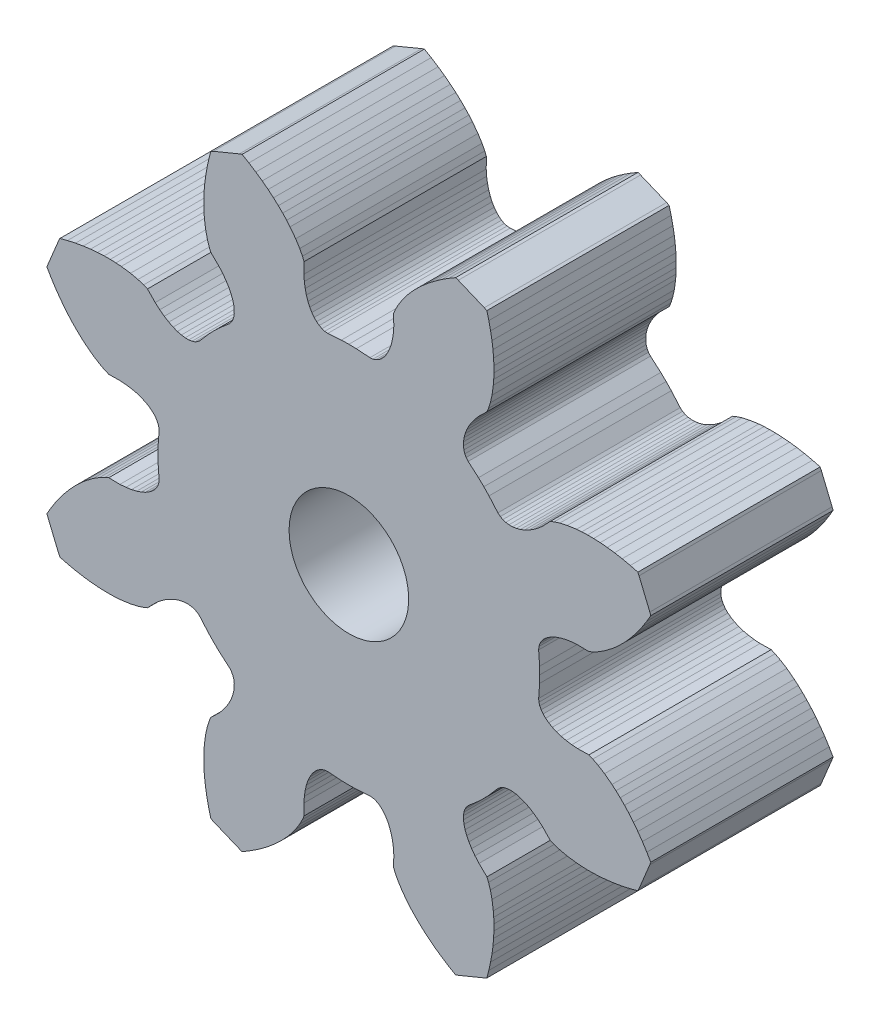
SolidWorks part; units mm, degrees
ref_plane "Front Plane" through (0, 0, 0) normal (0, 0, 1) x (1, 0, 0)
ref_plane "Top Plane" through (0, 0, 0) normal (0, 1, 0) x (1, 0, 0)
ref_plane "Right Plane" through (0, 0, 0) normal (1, 0, 0) x (0, 0, -1)
sketch "Sketch1" plane through (0, 0, 0) normal (0, 0, 1) x (1, 0, 0)
  line L0 (-6.534, 0.0723) -> (-6.5708, 0.241)
  line L1 (-6.5708, 0.241) -> (-6.599, 0.4026)
  line L2 (-6.599, 0.4026) -> (-6.6194, 0.5555)
  line L3 (-6.6194, 0.5555) -> (-6.6332, 0.701)
  line L4 (-6.6332, 0.701) -> (-6.6396, 0.8379)
  line L5 (-6.6396, 0.8379) -> (-6.6404, 0.9662)
  line L6 (-6.6404, 0.9662) -> (-6.6361, 1.0857)
  line L7 (-6.6361, 1.0857) -> (-6.6274, 1.1966)
  line L8 (-6.6274, 1.1966) -> (-6.6004, 1.3892)
  line L9 (-6.6004, 1.3892) -> (-6.5651, 1.5443)
  line L10 (-6.5651, 1.5443) -> (-6.5282, 1.6631)
  line L11 (-6.5282, 1.6631) -> (-6.494, 1.745)
  line L12 (-6.494, 1.745) -> (-6.3281, 1.9057)
  line L13 (-6.3281, 1.9057) -> (-6.2449, 2.0013)
  line L14 (-6.2449, 2.0013) -> (-6.1745, 2.0963)
  line L15 (-6.1745, 2.0963) -> (-6.1173, 2.1897)
  line L16 (-6.1173, 2.1897) -> (-6.0718, 2.2811)
  line L17 (-6.0718, 2.2811) -> (-6.0376, 2.3695)
  line L18 (-6.0376, 2.3695) -> (-6.0152, 2.4535)
  line L19 (-6.0152, 2.4535) -> (-6.0042, 2.5332)
  line L20 (-6.0042, 2.5332) -> (-6.0036, 2.607)
  line L21 (-6.0036, 2.607) -> (-6.0129, 2.6744)
  line L22 (-6.0129, 2.6744) -> (-6.0327, 2.7352)
  line L23 (-6.0327, 2.7352) -> (-6.0609, 2.7889)
  line L24 (-6.0609, 2.7889) -> (-6.1021, 2.8388)
  line L25 (-6.1021, 2.8388) -> (-6.3174, 3.0243)
  line L26 (-6.3174, 3.0243) -> (-6.4295, 3.133)
  line L27 (-6.4295, 3.133) -> (-6.5374, 3.2453)
  line L28 (-6.5374, 3.2453) -> (-6.7237, 3.4597)
  line L29 (-6.7237, 3.4597) -> (-6.7738, 3.5017)
  line L30 (-6.7738, 3.5017) -> (-6.8265, 3.53)
  line L31 (-6.8265, 3.53) -> (-6.8874, 3.5488)
  line L32 (-6.8874, 3.5488) -> (-6.9547, 3.5583)
  line L33 (-6.9547, 3.5583) -> (-7.0287, 3.5583)
  line L34 (-7.0287, 3.5583) -> (-7.1085, 3.5467)
  line L35 (-7.1085, 3.5467) -> (-7.1925, 3.5242)
  line L36 (-7.1925, 3.5242) -> (-7.2808, 3.4908)
  line L37 (-7.2808, 3.4908) -> (-7.372, 3.4452)
  line L38 (-7.372, 3.4452) -> (-7.4654, 3.3872)
  line L39 (-7.4654, 3.3872) -> (-7.5612, 3.317)
  line L40 (-7.5612, 3.317) -> (-7.6561, 3.2345)
  line L41 (-7.6561, 3.2345) -> (-7.8169, 3.0678)
  line L42 (-7.8169, 3.0678) -> (-7.8987, 3.0344)
  line L43 (-7.8987, 3.0344) -> (-8.0176, 2.9968)
  line L44 (-8.0176, 2.9968) -> (-8.1726, 2.9613)
  line L45 (-8.1726, 2.9613) -> (-8.3661, 2.9344)
  line L46 (-8.3661, 2.9344) -> (-8.4762, 2.9257)
  line L47 (-8.4762, 2.9257) -> (-8.5956, 2.9215)
  line L48 (-8.5956, 2.9215) -> (-8.7238, 2.9229)
  line L49 (-8.7238, 2.9229) -> (-8.8608, 2.9294)
  line L50 (-8.8608, 2.9294) -> (-9.0064, 2.9424)
  line L51 (-9.0064, 2.9424) -> (-9.1599, 2.9627)
  line L52 (-9.1599, 2.9627) -> (-9.3208, 2.991)
  line L53 (-9.3208, 2.991) -> (-9.4895, 3.0279)
  line L54 (-9.4895, 3.0279) -> (-9.6482, 3.07)
  line L55 (-9.6482, 3.07) -> (-9.6737, 3.1235)
  line L56 (-9.6737, 3.1235) -> (-9.8989, 3.6668)
  line L57 (-9.8989, 3.6668) -> (-9.9185, 3.722)
  line L58 (-9.9185, 3.722) -> (-9.836, 3.8639)
  line L59 (-9.836, 3.8639) -> (-9.7433, 4.0096)
  line L60 (-9.7433, 4.0096) -> (-9.649, 4.1435)
  line L61 (-9.649, 4.1435) -> (-9.5548, 4.266)
  line L62 (-9.5548, 4.266) -> (-9.4613, 4.3783)
  line L63 (-9.4613, 4.3783) -> (-9.3693, 4.4797)
  line L64 (-9.3693, 4.4797) -> (-9.2789, 4.5709)
  line L65 (-9.2789, 4.5709) -> (-9.1912, 4.6528)
  line L66 (-9.1912, 4.6528) -> (-9.1072, 4.7246)
  line L67 (-9.1072, 4.7246) -> (-8.952, 4.842)
  line L68 (-8.952, 4.842) -> (-8.8173, 4.9268)
  line L69 (-8.8173, 4.9268) -> (-8.7066, 4.9838)
  line L70 (-8.7066, 4.9838) -> (-8.6253, 5.0188)
  line L71 (-8.6253, 5.0188) -> (-8.3935, 5.0143)
  line L72 (-8.3935, 5.0143) -> (-8.2675, 5.0237)
  line L73 (-8.2675, 5.0237) -> (-8.151, 5.0412)
  line L74 (-8.151, 5.0412) -> (-8.0435, 5.0665)
  line L75 (-8.0435, 5.0665) -> (-7.9472, 5.0983)
  line L76 (-7.9472, 5.0983) -> (-7.8611, 5.1367)
  line L77 (-7.8611, 5.1367) -> (-7.7858, 5.181)
  line L78 (-7.7858, 5.181) -> (-7.7211, 5.2287)
  line L79 (-7.7211, 5.2287) -> (-7.6684, 5.2809)
  line L80 (-7.6684, 5.2809) -> (-7.627, 5.3361)
  line L81 (-7.627, 5.3361) -> (-7.598, 5.3924)
  line L82 (-7.598, 5.3924) -> (-7.5807, 5.4497)
  line L83 (-7.5807, 5.4497) -> (-7.5749, 5.5143)
  line L84 (-7.5749, 5.5143) -> (-7.5952, 5.7982)
  line L85 (-7.5952, 5.7982) -> (-7.598, 5.954)
  line L86 (-7.598, 5.954) -> (-7.5952, 6.1096)
  line L87 (-7.5952, 6.1096) -> (-7.5749, 6.3929)
  line L88 (-7.5749, 6.3929) -> (-7.5807, 6.4581)
  line L89 (-7.5807, 6.4581) -> (-7.598, 6.5154)
  line L90 (-7.598, 6.5154) -> (-7.627, 6.572)
  line L91 (-7.627, 6.572) -> (-7.6684, 6.627)
  line L92 (-7.6684, 6.627) -> (-7.7211, 6.6784)
  line L93 (-7.7211, 6.6784) -> (-7.7858, 6.727)
  line L94 (-7.7858, 6.727) -> (-7.8611, 6.7704)
  line L95 (-7.8611, 6.7704) -> (-7.9472, 6.8087)
  line L96 (-7.9472, 6.8087) -> (-8.0435, 6.8415)
  line L97 (-8.0435, 6.8415) -> (-8.151, 6.8668)
  line L98 (-8.151, 6.8668) -> (-8.2675, 6.8841)
  line L99 (-8.2675, 6.8841) -> (-8.3935, 6.8927)
  line L100 (-8.3935, 6.8927) -> (-8.6253, 6.8893)
  line L101 (-8.6253, 6.8893) -> (-8.7066, 6.9232)
  line L102 (-8.7066, 6.9232) -> (-8.8173, 6.9813)
  line L103 (-8.8173, 6.9813) -> (-8.952, 7.0661)
  line L104 (-8.952, 7.0661) -> (-9.1072, 7.1834)
  line L105 (-9.1072, 7.1834) -> (-9.1912, 7.255)
  line L106 (-9.1912, 7.255) -> (-9.2789, 7.337)
  line L107 (-9.2789, 7.337) -> (-9.3693, 7.4274)
  line L108 (-9.3693, 7.4274) -> (-9.4613, 7.5289)
  line L109 (-9.4613, 7.5289) -> (-9.5548, 7.6418)
  line L110 (-9.5548, 7.6418) -> (-9.649, 7.7643)
  line L111 (-9.649, 7.7643) -> (-9.7433, 7.8983)
  line L112 (-9.7433, 7.8983) -> (-9.836, 8.0439)
  line L113 (-9.836, 8.0439) -> (-9.9185, 8.1852)
  line L114 (-9.9185, 8.1852) -> (-9.8989, 8.2411)
  line L115 (-9.8989, 8.2411) -> (-9.6737, 8.785)
  line L116 (-9.6737, 8.785) -> (-9.6482, 8.8378)
  line L117 (-9.6482, 8.8378) -> (-9.4895, 8.8799)
  line L118 (-9.4895, 8.8799) -> (-9.3208, 8.9169)
  line L119 (-9.3208, 8.9169) -> (-9.1599, 8.9452)
  line L120 (-9.1599, 8.9452) -> (-9.0064, 8.9654)
  line L121 (-9.0064, 8.9654) -> (-8.8608, 8.9784)
  line L122 (-8.8608, 8.9784) -> (-8.7238, 8.9849)
  line L123 (-8.7238, 8.9849) -> (-8.5956, 8.9857)
  line L124 (-8.5956, 8.9857) -> (-8.4762, 8.9814)
  line L125 (-8.4762, 8.9814) -> (-8.3661, 8.9734)
  line L126 (-8.3661, 8.9734) -> (-8.1726, 8.9457)
  line L127 (-8.1726, 8.9457) -> (-8.0176, 8.9111)
  line L128 (-8.0176, 8.9111) -> (-7.8987, 8.8735)
  line L129 (-7.8987, 8.8735) -> (-7.8169, 8.8401)
  line L130 (-7.8169, 8.8401) -> (-7.6561, 8.6735)
  line L131 (-7.6561, 8.6735) -> (-7.5612, 8.5908)
  line L132 (-7.5612, 8.5908) -> (-7.4654, 8.5206)
  line L133 (-7.4654, 8.5206) -> (-7.372, 8.4626)
  line L134 (-7.372, 8.4626) -> (-7.2808, 8.4171)
  line L135 (-7.2808, 8.4171) -> (-7.1925, 8.3829)
  line L136 (-7.1925, 8.3829) -> (-7.1085, 8.3613)
  line L137 (-7.1085, 8.3613) -> (-7.0287, 8.3497)
  line L138 (-7.0287, 8.3497) -> (-6.9547, 8.349)
  line L139 (-6.9547, 8.349) -> (-6.8874, 8.359)
  line L140 (-6.8874, 8.359) -> (-6.8265, 8.3778)
  line L141 (-6.8265, 8.3778) -> (-6.7738, 8.4061)
  line L142 (-6.7738, 8.4061) -> (-6.7237, 8.4482)
  line L143 (-6.7237, 8.4482) -> (-6.5374, 8.6625)
  line L144 (-6.5374, 8.6625) -> (-6.4295, 8.7749)
  line L145 (-6.4295, 8.7749) -> (-6.3174, 8.8828)
  line L146 (-6.3174, 8.8828) -> (-6.1021, 9.0691)
  line L147 (-6.1021, 9.0691) -> (-6.0609, 9.119)
  line L148 (-6.0609, 9.119) -> (-6.0327, 9.1718)
  line L149 (-6.0327, 9.1718) -> (-6.0129, 9.2327)
  line L150 (-6.0129, 9.2327) -> (-6.0036, 9.3009)
  line L151 (-6.0036, 9.3009) -> (-6.0042, 9.3748)
  line L152 (-6.0042, 9.3748) -> (-6.0152, 9.4545)
  line L153 (-6.0152, 9.4545) -> (-6.0376, 9.5385)
  line L154 (-6.0376, 9.5385) -> (-6.0718, 9.6267)
  line L155 (-6.0718, 9.6267) -> (-6.1173, 9.7182)
  line L156 (-6.1173, 9.7182) -> (-6.1745, 9.8115)
  line L157 (-6.1745, 9.8115) -> (-6.2449, 9.9065)
  line L158 (-6.2449, 9.9065) -> (-6.3281, 10.0021)
  line L159 (-6.3281, 10.0021) -> (-6.494, 10.163)
  line L160 (-6.494, 10.163) -> (-6.5282, 10.2447)
  line L161 (-6.5282, 10.2447) -> (-6.5651, 10.3635)
  line L162 (-6.5651, 10.3635) -> (-6.6004, 10.5186)
  line L163 (-6.6004, 10.5186) -> (-6.6274, 10.7114)
  line L164 (-6.6274, 10.7114) -> (-6.6361, 10.8214)
  line L165 (-6.6361, 10.8214) -> (-6.6404, 10.9417)
  line L166 (-6.6404, 10.9417) -> (-6.6396, 11.07)
  line L167 (-6.6396, 11.07) -> (-6.6332, 11.2061)
  line L168 (-6.6332, 11.2061) -> (-6.6194, 11.3524)
  line L169 (-6.6194, 11.3524) -> (-6.599, 11.5052)
  line L170 (-6.599, 11.5052) -> (-6.5708, 11.6668)
  line L171 (-6.5708, 11.6668) -> (-6.534, 11.835)
  line L172 (-6.534, 11.835) -> (-6.4926, 11.9943)
  line L173 (-6.4926, 11.9943) -> (-6.4397, 12.0197)
  line L174 (-6.4397, 12.0197) -> (-5.8956, 12.2451)
  line L175 (-5.8956, 12.2451) -> (-5.84, 12.2644)
  line L176 (-5.84, 12.2644) -> (-5.6979, 12.1812)
  line L177 (-5.6979, 12.1812) -> (-5.5531, 12.0884)
  line L178 (-5.5531, 12.0884) -> (-5.419, 11.9943)
  line L179 (-5.419, 11.9943) -> (-5.2959, 11.9008)
  line L180 (-5.2959, 11.9008) -> (-5.1836, 11.8066)
  line L181 (-5.1836, 11.8066) -> (-5.0822, 11.7146)
  line L182 (-5.0822, 11.7146) -> (-4.9909, 11.6248)
  line L183 (-4.9909, 11.6248) -> (-4.9089, 11.5371)
  line L184 (-4.9089, 11.5371) -> (-4.8372, 11.4531)
  line L185 (-4.8372, 11.4531) -> (-4.72, 11.2973)
  line L186 (-4.72, 11.2973) -> (-4.6352, 11.1627)
  line L187 (-4.6352, 11.1627) -> (-4.5779, 11.0525)
  line L188 (-4.5779, 11.0525) -> (-4.5438, 10.9705)
  line L189 (-4.5438, 10.9705) -> (-4.5475, 10.7395)
  line L190 (-4.5475, 10.7395) -> (-4.5388, 10.6136)
  line L191 (-4.5388, 10.6136) -> (-4.5206, 10.4961)
  line L192 (-4.5206, 10.4961) -> (-4.4962, 10.3897)
  line L193 (-4.4962, 10.3897) -> (-4.4635, 10.2925)
  line L194 (-4.4635, 10.2925) -> (-4.4251, 10.2064)
  line L195 (-4.4251, 10.2064) -> (-4.3808, 10.1311)
  line L196 (-4.3808, 10.1311) -> (-4.3331, 10.0664)
  line L197 (-4.3331, 10.0664) -> (-4.2808, 10.0144)
  line L198 (-4.2808, 10.0144) -> (-4.2265, 9.9732)
  line L199 (-4.2265, 9.9732) -> (-4.1701, 9.9433)
  line L200 (-4.1701, 9.9433) -> (-4.112, 9.9261)
  line L201 (-4.112, 9.9261) -> (-4.0477, 9.9201)
  line L202 (-4.0477, 9.9201) -> (-3.7643, 9.9405)
  line L203 (-3.7643, 9.9405) -> (-3.6079, 9.9433)
  line L204 (-3.6079, 9.9433) -> (-3.4523, 9.9405)
  line L205 (-3.4523, 9.9405) -> (-3.1688, 9.9201)
  line L206 (-3.1688, 9.9201) -> (-3.1044, 9.9261)
  line L207 (-3.1044, 9.9261) -> (-3.0465, 9.9433)
  line L208 (-3.0465, 9.9433) -> (-2.9898, 9.9732)
  line L209 (-2.9898, 9.9732) -> (-2.9358, 10.0144)
  line L210 (-2.9358, 10.0144) -> (-2.8834, 10.0664)
  line L211 (-2.8834, 10.0664) -> (-2.835, 10.1311)
  line L212 (-2.835, 10.1311) -> (-2.7914, 10.2064)
  line L213 (-2.7914, 10.2064) -> (-2.7531, 10.2925)
  line L214 (-2.7531, 10.2925) -> (-2.7204, 10.3897)
  line L215 (-2.7204, 10.3897) -> (-2.6952, 10.4961)
  line L216 (-2.6952, 10.4961) -> (-2.6778, 10.6136)
  line L217 (-2.6778, 10.6136) -> (-2.669, 10.7395)
  line L218 (-2.669, 10.7395) -> (-2.6727, 10.9705)
  line L219 (-2.6727, 10.9705) -> (-2.6387, 11.0525)
  line L220 (-2.6387, 11.0525) -> (-2.5813, 11.1627)
  line L221 (-2.5813, 11.1627) -> (-2.4966, 11.2973)
  line L222 (-2.4966, 11.2973) -> (-2.3794, 11.4531)
  line L223 (-2.3794, 11.4531) -> (-2.3069, 11.5371)
  line L224 (-2.3069, 11.5371) -> (-2.2255, 11.6248)
  line L225 (-2.2255, 11.6248) -> (-2.1343, 11.7146)
  line L226 (-2.1343, 11.7146) -> (-2.0329, 11.8066)
  line L227 (-2.0329, 11.8066) -> (-1.9207, 11.9008)
  line L228 (-1.9207, 11.9008) -> (-1.7976, 11.9943)
  line L229 (-1.7976, 11.9943) -> (-1.6635, 12.0884)
  line L230 (-1.6635, 12.0884) -> (-1.5186, 12.1812)
  line L231 (-1.5186, 12.1812) -> (-1.3766, 12.2644)
  line L232 (-1.3766, 12.2644) -> (-1.3215, 12.2451)
  line L233 (-1.3215, 12.2451) -> (-0.7776, 12.0197)
  line L234 (-0.7776, 12.0197) -> (-0.724, 11.9943)
  line L235 (-0.724, 11.9943) -> (-0.6826, 11.835)
  line L236 (-0.6826, 11.835) -> (-0.6458, 11.6668)
  line L237 (-0.6458, 11.6668) -> (-0.6168, 11.5052)
  line L238 (-0.6168, 11.5052) -> (-0.5964, 11.3524)
  line L239 (-0.5964, 11.3524) -> (-0.5834, 11.2061)
  line L240 (-0.5834, 11.2061) -> (-0.5769, 11.07)
  line L241 (-0.5769, 11.07) -> (-0.5762, 10.9417)
  line L242 (-0.5762, 10.9417) -> (-0.5805, 10.8214)
  line L243 (-0.5805, 10.8214) -> (-0.5891, 10.7114)
  line L244 (-0.5891, 10.7114) -> (-0.616, 10.5186)
  line L245 (-0.616, 10.5186) -> (-0.6507, 10.3635)
  line L246 (-0.6507, 10.3635) -> (-0.6884, 10.2447)
  line L247 (-0.6884, 10.2447) -> (-0.7225, 10.163)
  line L248 (-0.7225, 10.163) -> (-0.8883, 10.0021)
  line L249 (-0.8883, 10.0021) -> (-0.9717, 9.9065)
  line L250 (-0.9717, 9.9065) -> (-1.0413, 9.8115)
  line L251 (-1.0413, 9.8115) -> (-1.0991, 9.7182)
  line L252 (-1.0991, 9.7182) -> (-1.1448, 9.6267)
  line L253 (-1.1448, 9.6267) -> (-1.1789, 9.5385)
  line L254 (-1.1789, 9.5385) -> (-1.2014, 9.4545)
  line L255 (-1.2014, 9.4545) -> (-1.2123, 9.3748)
  line L256 (-1.2123, 9.3748) -> (-1.2129, 9.3009)
  line L257 (-1.2129, 9.3009) -> (-1.2035, 9.2327)
  line L258 (-1.2035, 9.2327) -> (-1.1839, 9.1718)
  line L259 (-1.1839, 9.1718) -> (-1.1557, 9.119)
  line L260 (-1.1557, 9.119) -> (-1.1143, 9.0691)
  line L261 (-1.1143, 9.0691) -> (-0.8992, 8.8828)
  line L262 (-0.8992, 8.8828) -> (-0.787, 8.7749)
  line L263 (-0.787, 8.7749) -> (-0.6791, 8.6625)
  line L264 (-0.6791, 8.6625) -> (-0.4929, 8.4482)
  line L265 (-0.4929, 8.4482) -> (-0.4428, 8.4061)
  line L266 (-0.4428, 8.4061) -> (-0.3899, 8.3778)
  line L267 (-0.3899, 8.3778) -> (-0.3292, 8.359)
  line L268 (-0.3292, 8.359) -> (-0.2619, 8.349)
  line L269 (-0.2619, 8.349) -> (-0.1871, 8.3497)
  line L270 (-0.1871, 8.3497) -> (-0.108, 8.3613)
  line L271 (-0.108, 8.3613) -> (-0.0233, 8.3829)
  line L272 (-0.0233, 8.3829) -> (0.0642, 8.4171)
  line L273 (0.0642, 8.4171) -> (0.1554, 8.4626)
  line L274 (0.1554, 8.4626) -> (0.2497, 8.5206)
  line L275 (0.2497, 8.5206) -> (0.3446, 8.5908)
  line L276 (0.3446, 8.5908) -> (0.4404, 8.6735)
  line L277 (0.4404, 8.6735) -> (0.6003, 8.8401)
  line L278 (0.6003, 8.8401) -> (0.6822, 8.8735)
  line L279 (0.6822, 8.8735) -> (0.801, 8.9111)
  line L280 (0.801, 8.9111) -> (0.9568, 8.9457)
  line L281 (0.9568, 8.9457) -> (1.1495, 8.9734)
  line L282 (1.1495, 8.9734) -> (1.2597, 8.9814)
  line L283 (1.2597, 8.9814) -> (1.3791, 8.9857)
  line L284 (1.3791, 8.9857) -> (1.5074, 8.9849)
  line L285 (1.5074, 8.9849) -> (1.6442, 8.9784)
  line L286 (1.6442, 8.9784) -> (1.7906, 8.9654)
  line L287 (1.7906, 8.9654) -> (1.9435, 8.9452)
  line L288 (1.9435, 8.9452) -> (2.1042, 8.9169)
  line L289 (2.1042, 8.9169) -> (2.273, 8.8799)
  line L290 (2.273, 8.8799) -> (2.4318, 8.8378)
  line L291 (2.4318, 8.8378) -> (2.4572, 8.785)
  line L292 (2.4572, 8.785) -> (2.6823, 8.2411)
  line L293 (2.6823, 8.2411) -> (2.7019, 8.1852)
  line L294 (2.7019, 8.1852) -> (2.6194, 8.0439)
  line L295 (2.6194, 8.0439) -> (2.5267, 7.8983)
  line L296 (2.5267, 7.8983) -> (2.4325, 7.7643)
  line L297 (2.4325, 7.7643) -> (2.3383, 7.6418)
  line L298 (2.3383, 7.6418) -> (2.2449, 7.5289)
  line L299 (2.2449, 7.5289) -> (2.1529, 7.4274)
  line L300 (2.1529, 7.4274) -> (2.0623, 7.337)
  line L301 (2.0623, 7.337) -> (1.9746, 7.255)
  line L302 (1.9746, 7.255) -> (1.8906, 7.1834)
  line L303 (1.8906, 7.1834) -> (1.7356, 7.0661)
  line L304 (1.7356, 7.0661) -> (1.6007, 6.9813)
  line L305 (1.6007, 6.9813) -> (1.49, 6.9232)
  line L306 (1.49, 6.9232) -> (1.4088, 6.8893)
  line L307 (1.4088, 6.8893) -> (1.1769, 6.8927)
  line L308 (1.1769, 6.8927) -> (1.051, 6.8841)
  line L309 (1.051, 6.8841) -> (0.9344, 6.8668)
  line L310 (0.9344, 6.8668) -> (0.8272, 6.8415)
  line L311 (0.8272, 6.8415) -> (0.7308, 6.8087)
  line L312 (0.7308, 6.8087) -> (0.6445, 6.7704)
  line L313 (0.6445, 6.7704) -> (0.5692, 6.727)
  line L314 (0.5692, 6.727) -> (0.5047, 6.6784)
  line L315 (0.5047, 6.6784) -> (0.4518, 6.627)
  line L316 (0.4518, 6.627) -> (0.4112, 6.572)
  line L317 (0.4112, 6.572) -> (0.3816, 6.5154)
  line L318 (0.3816, 6.5154) -> (0.3641, 6.4581)
  line L319 (0.3641, 6.4581) -> (0.3584, 6.3929)
  line L320 (0.3584, 6.3929) -> (0.3788, 6.1096)
  line L321 (0.3788, 6.1096) -> (0.3816, 5.954)
  line L322 (0.3816, 5.954) -> (0.3788, 5.7982)
  line L323 (0.3788, 5.7982) -> (0.3584, 5.5143)
  line L324 (0.3584, 5.5143) -> (0.3641, 5.4497)
  line L325 (0.3641, 5.4497) -> (0.3816, 5.3924)
  line L326 (0.3816, 5.3924) -> (0.4112, 5.3361)
  line L327 (0.4112, 5.3361) -> (0.4518, 5.2809)
  line L328 (0.4518, 5.2809) -> (0.5047, 5.2287)
  line L329 (0.5047, 5.2287) -> (0.5692, 5.181)
  line L330 (0.5692, 5.181) -> (0.6445, 5.1367)
  line L331 (0.6445, 5.1367) -> (0.7308, 5.0983)
  line L332 (0.7308, 5.0983) -> (0.8272, 5.0665)
  line L333 (0.8272, 5.0665) -> (0.9344, 5.0412)
  line L334 (0.9344, 5.0412) -> (1.051, 5.0237)
  line L335 (1.051, 5.0237) -> (1.1769, 5.0143)
  line L336 (1.1769, 5.0143) -> (1.4088, 5.0188)
  line L337 (1.4088, 5.0188) -> (1.49, 4.9838)
  line L338 (1.49, 4.9838) -> (1.6007, 4.9268)
  line L339 (1.6007, 4.9268) -> (1.7356, 4.842)
  line L340 (1.7356, 4.842) -> (1.8906, 4.7246)
  line L341 (1.8906, 4.7246) -> (1.9746, 4.6528)
  line L342 (1.9746, 4.6528) -> (2.0623, 4.5709)
  line L343 (2.0623, 4.5709) -> (2.1529, 4.4797)
  line L344 (2.1529, 4.4797) -> (2.2449, 4.3783)
  line L345 (2.2449, 4.3783) -> (2.3383, 4.266)
  line L346 (2.3383, 4.266) -> (2.4325, 4.1435)
  line L347 (2.4325, 4.1435) -> (2.5267, 4.0096)
  line L348 (2.5267, 4.0096) -> (2.6194, 3.8639)
  line L349 (2.6194, 3.8639) -> (2.7019, 3.722)
  line L350 (2.7019, 3.722) -> (2.6823, 3.6668)
  line L351 (2.6823, 3.6668) -> (2.4572, 3.1235)
  line L352 (2.4572, 3.1235) -> (2.4318, 3.07)
  line L353 (2.4318, 3.07) -> (2.273, 3.0279)
  line L354 (2.273, 3.0279) -> (2.1042, 2.991)
  line L355 (2.1042, 2.991) -> (1.9435, 2.9627)
  line L356 (1.9435, 2.9627) -> (1.7906, 2.9424)
  line L357 (1.7906, 2.9424) -> (1.6442, 2.9294)
  line L358 (1.6442, 2.9294) -> (1.5074, 2.9229)
  line L359 (1.5074, 2.9229) -> (1.3791, 2.9215)
  line L360 (1.3791, 2.9215) -> (1.2597, 2.9257)
  line L361 (1.2597, 2.9257) -> (1.1495, 2.9344)
  line L362 (1.1495, 2.9344) -> (0.9568, 2.9613)
  line L363 (0.9568, 2.9613) -> (0.801, 2.9968)
  line L364 (0.801, 2.9968) -> (0.6822, 3.0344)
  line L365 (0.6822, 3.0344) -> (0.6003, 3.0678)
  line L366 (0.6003, 3.0678) -> (0.4404, 3.2345)
  line L367 (0.4404, 3.2345) -> (0.3446, 3.317)
  line L368 (0.3446, 3.317) -> (0.2497, 3.3872)
  line L369 (0.2497, 3.3872) -> (0.1554, 3.4452)
  line L370 (0.1554, 3.4452) -> (0.0642, 3.4908)
  line L371 (0.0642, 3.4908) -> (-0.0233, 3.5242)
  line L372 (-0.0233, 3.5242) -> (-0.108, 3.5467)
  line L373 (-0.108, 3.5467) -> (-0.1871, 3.5583)
  line L374 (-0.1871, 3.5583) -> (-0.2619, 3.5583)
  line L375 (-0.2619, 3.5583) -> (-0.3292, 3.5488)
  line L376 (-0.3292, 3.5488) -> (-0.3899, 3.53)
  line L377 (-0.3899, 3.53) -> (-0.4428, 3.5017)
  line L378 (-0.4428, 3.5017) -> (-0.4929, 3.4597)
  line L379 (-0.4929, 3.4597) -> (-0.6791, 3.2453)
  line L380 (-0.6791, 3.2453) -> (-0.787, 3.133)
  line L381 (-0.787, 3.133) -> (-0.8992, 3.0243)
  line L382 (-0.8992, 3.0243) -> (-1.1143, 2.8388)
  line L383 (-1.1143, 2.8388) -> (-1.1557, 2.7889)
  line L384 (-1.1557, 2.7889) -> (-1.1839, 2.7352)
  line L385 (-1.1839, 2.7352) -> (-1.2035, 2.6744)
  line L386 (-1.2035, 2.6744) -> (-1.2129, 2.607)
  line L387 (-1.2129, 2.607) -> (-1.2123, 2.5332)
  line L388 (-1.2123, 2.5332) -> (-1.2014, 2.4535)
  line L389 (-1.2014, 2.4535) -> (-1.1789, 2.3695)
  line L390 (-1.1789, 2.3695) -> (-1.1448, 2.2811)
  line L391 (-1.1448, 2.2811) -> (-1.0991, 2.1897)
  line L392 (-1.0991, 2.1897) -> (-1.0413, 2.0963)
  line L393 (-1.0413, 2.0963) -> (-0.9717, 2.0013)
  line L394 (-0.9717, 2.0013) -> (-0.8883, 1.9057)
  line L395 (-0.8883, 1.9057) -> (-0.7225, 1.745)
  line L396 (-0.7225, 1.745) -> (-0.6884, 1.6631)
  line L397 (-0.6884, 1.6631) -> (-0.6507, 1.5443)
  line L398 (-0.6507, 1.5443) -> (-0.616, 1.3892)
  line L399 (-0.616, 1.3892) -> (-0.5891, 1.1966)
  line L400 (-0.5891, 1.1966) -> (-0.5805, 1.0857)
  line L401 (-0.5805, 1.0857) -> (-0.5762, 0.9662)
  line L402 (-0.5762, 0.9662) -> (-0.5769, 0.8379)
  line L403 (-0.5769, 0.8379) -> (-0.5834, 0.701)
  line L404 (-0.5834, 0.701) -> (-0.5964, 0.5555)
  line L405 (-0.5964, 0.5555) -> (-0.6168, 0.4026)
  line L406 (-0.6168, 0.4026) -> (-0.6458, 0.241)
  line L407 (-0.6458, 0.241) -> (-0.6826, 0.0723)
  line L408 (-0.6826, 0.0723) -> (-0.724, -0.0864)
  line L409 (-0.724, -0.0864) -> (-0.7776, -0.1117)
  line L410 (-0.7776, -0.1117) -> (-1.3215, -0.3363)
  line L411 (-1.3215, -0.3363) -> (-1.3766, -0.3566)
  line L412 (-1.3766, -0.3566) -> (-1.5186, -0.274)
  line L413 (-1.5186, -0.274) -> (-1.6635, -0.1806)
  line L414 (-1.6635, -0.1806) -> (-1.7976, -0.0872)
  line L415 (-1.7976, -0.0872) -> (-1.9207, 0.0071)
  line L416 (-1.9207, 0.0071) -> (-2.0329, 0.1012)
  line L417 (-2.0329, 0.1012) -> (-2.1343, 0.1932)
  line L418 (-2.1343, 0.1932) -> (-2.2255, 0.2831)
  line L419 (-2.2255, 0.2831) -> (-2.3069, 0.3707)
  line L420 (-2.3069, 0.3707) -> (-2.3794, 0.4547)
  line L421 (-2.3794, 0.4547) -> (-2.4966, 0.6105)
  line L422 (-2.4966, 0.6105) -> (-2.5813, 0.7446)
  line L423 (-2.5813, 0.7446) -> (-2.6387, 0.8554)
  line L424 (-2.6387, 0.8554) -> (-2.6727, 0.9372)
  line L425 (-2.6727, 0.9372) -> (-2.669, 1.1683)
  line L426 (-2.669, 1.1683) -> (-2.6778, 1.2943)
  line L427 (-2.6778, 1.2943) -> (-2.6952, 1.411)
  line L428 (-2.6952, 1.411) -> (-2.7204, 1.5182)
  line L429 (-2.7204, 1.5182) -> (-2.7531, 1.6153)
  line L430 (-2.7531, 1.6153) -> (-2.7914, 1.7014)
  line L431 (-2.7914, 1.7014) -> (-2.835, 1.7769)
  line L432 (-2.835, 1.7769) -> (-2.8834, 1.8406)
  line L433 (-2.8834, 1.8406) -> (-2.9358, 1.8934)
  line L434 (-2.9358, 1.8934) -> (-2.9898, 1.9347)
  line L435 (-2.9898, 1.9347) -> (-3.0465, 1.9637)
  line L436 (-3.0465, 1.9637) -> (-3.1044, 1.9818)
  line L437 (-3.1044, 1.9818) -> (-3.1688, 1.9876)
  line L438 (-3.1688, 1.9876) -> (-3.4523, 1.9673)
  line L439 (-3.4523, 1.9673) -> (-3.6079, 1.9637)
  line L440 (-3.6079, 1.9637) -> (-3.7643, 1.9673)
  line L441 (-3.7643, 1.9673) -> (-4.0477, 1.9876)
  line L442 (-4.0477, 1.9876) -> (-4.112, 1.9818)
  line L443 (-4.112, 1.9818) -> (-4.1701, 1.9637)
  line L444 (-4.1701, 1.9637) -> (-4.2265, 1.9347)
  line L445 (-4.2265, 1.9347) -> (-4.2808, 1.8934)
  line L446 (-4.2808, 1.8934) -> (-4.3331, 1.8406)
  line L447 (-4.3331, 1.8406) -> (-4.3808, 1.7769)
  line L448 (-4.3808, 1.7769) -> (-4.4251, 1.7014)
  line L449 (-4.4251, 1.7014) -> (-4.4635, 1.6153)
  line L450 (-4.4635, 1.6153) -> (-4.4962, 1.5182)
  line L451 (-4.4962, 1.5182) -> (-4.5206, 1.411)
  line L452 (-4.5206, 1.411) -> (-4.5388, 1.2943)
  line L453 (-4.5388, 1.2943) -> (-4.5475, 1.1683)
  line L454 (-4.5475, 1.1683) -> (-4.5438, 0.9372)
  line L455 (-4.5438, 0.9372) -> (-4.5779, 0.8554)
  line L456 (-4.5779, 0.8554) -> (-4.6352, 0.7446)
  line L457 (-4.6352, 0.7446) -> (-4.72, 0.6105)
  line L458 (-4.72, 0.6105) -> (-4.8372, 0.4547)
  line L459 (-4.8372, 0.4547) -> (-4.9089, 0.3707)
  line L460 (-4.9089, 0.3707) -> (-4.9909, 0.2831)
  line L461 (-4.9909, 0.2831) -> (-5.0822, 0.1932)
  line L462 (-5.0822, 0.1932) -> (-5.1836, 0.1012)
  line L463 (-5.1836, 0.1012) -> (-5.2959, 0.0071)
  line L464 (-5.2959, 0.0071) -> (-5.419, -0.0872)
  line L465 (-5.419, -0.0872) -> (-5.5531, -0.1806)
  line L466 (-5.5531, -0.1806) -> (-5.6979, -0.274)
  line L467 (-5.6979, -0.274) -> (-5.84, -0.3566)
  line L468 (-5.84, -0.3566) -> (-5.8956, -0.3363)
  line L469 (-5.8956, -0.3363) -> (-6.4397, -0.1117)
  line L470 (-6.4397, -0.1117) -> (-6.4926, -0.0864)
  line L471 (-6.4926, -0.0864) -> (-6.534, 0.0723)
  circle A0 centre (-3.6079, 5.954) radius 1.25
  dimension "D1" = 2.5
extrude "Boss-Extrude1" add sketch "Sketch1" along normal blind 3.81
